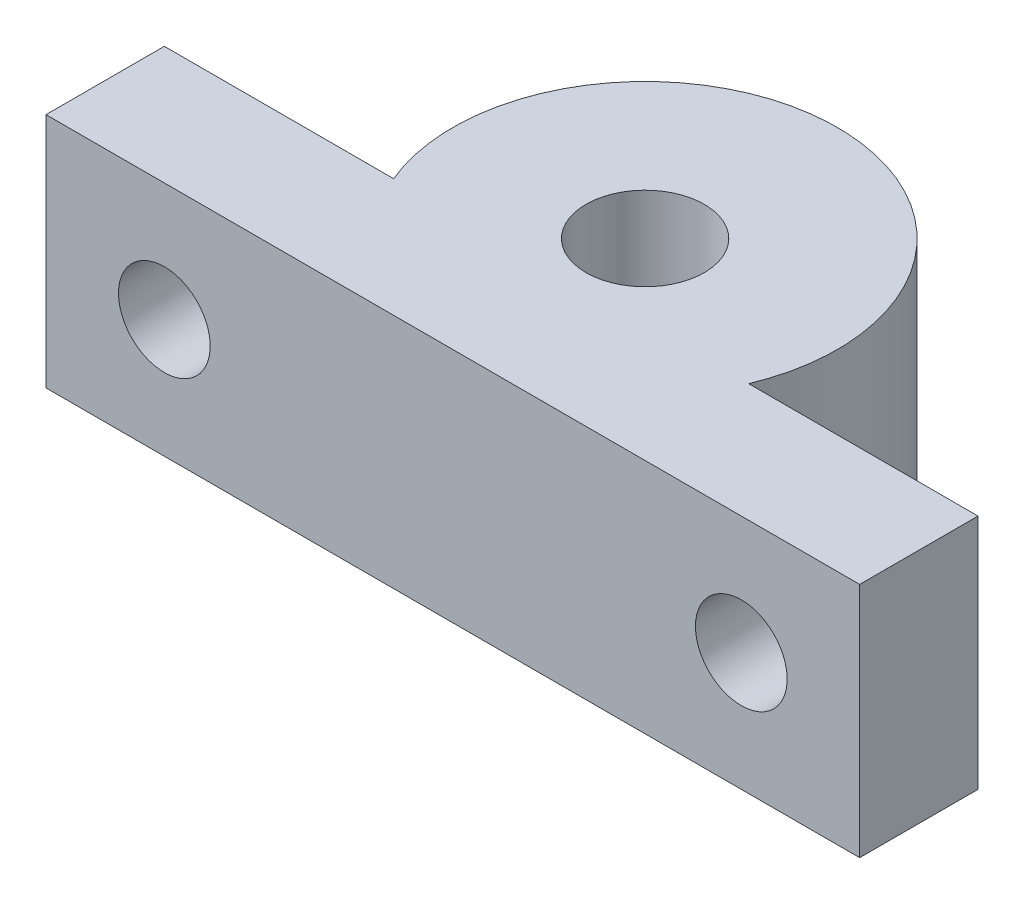
SolidWorks part; units mm, degrees
ref_plane "Front Plane" through (0, 0, 0) normal (0, 0, 1) x (1, 0, 0)
ref_plane "Top Plane" through (0, 0, 0) normal (0, 1, 0) x (1, 0, 0)
ref_plane "Right Plane" through (0, 0, 0) normal (1, 0, 0) x (0, 0, -1)
sketch "Sketch1" plane through (0, 0, 0) normal (0, 1, 0) x (1, 0, 0)
  circle A1 centre (0, 0) radius 6.5
  dimension "D1" = 13
extrude "Boss-Extrude1" add sketch "Sketch1" along normal blind 8
sketch "Sketch2" plane through (0, 8, 0) normal (0, 1, 0) x (1, 0, 0)
  line L0 (0, 0) -> (0, -6.5)
  circle A0 centre (0, 0) radius 6.5 construction
ref_plane "Plane1" through (0, 8, 6.5) normal (0, 0, 1) x (1, 0, 0)
sketch "Sketch3" plane through (0, 8, 6.5) normal (0, 0, 1) x (1, 0, 0)
  line L0 (-13.75, 0) -> (13.75, 0)
  line L1 (13.75, 0) -> (13.75, -8)
  line L2 (13.75, -8) -> (-13.75, -8)
  line L3 (-13.75, -8) -> (-13.75, 0)
  line L4 (-6.5, 0) -> (-6.5, -8) construction
  line L5 (6.5, 0) -> (-6.5, 0) construction
  dimension "D1" = 8
  dimension "D2" = 27.5
  dimension "D3" = 7.25
  dimension "D4" = 0
extrude "Boss-Extrude2" add sketch "Sketch3" against normal blind 4
sketch "Sketch4" plane through (0, 8, 0) normal (0, 1, 0) x (1, 0, 0)
  circle A0 centre (0, 0) radius 2
  dimension "D1" = 4
extrude "Cut-Extrude1" cut sketch "Sketch4" against normal up to next
sketch "Sketch5" plane through (0, 0, 2.5) normal (0, 0, -1) x (-1, 0, 0)
  line L0 (13.75, 8) -> (13.75, 0) construction
  line L1 (6, 8) -> (13.75, 8) construction
  line L2 (-13.75, 0) -> (-13.75, 8) construction
  line L3 (-6, 0) -> (-13.75, 0) construction
  circle A0 centre (9.75, 4) radius 1.55
  circle A1 centre (-9.75, 4) radius 1.55
  dimension "D1" = 3.1
  dimension "D4" = 4
  dimension "D2" = 4
  dimension "D3" = 4
  dimension "D5" = 4
extrude "Cut-Extrude2" cut sketch "Sketch5" against normal up to next
